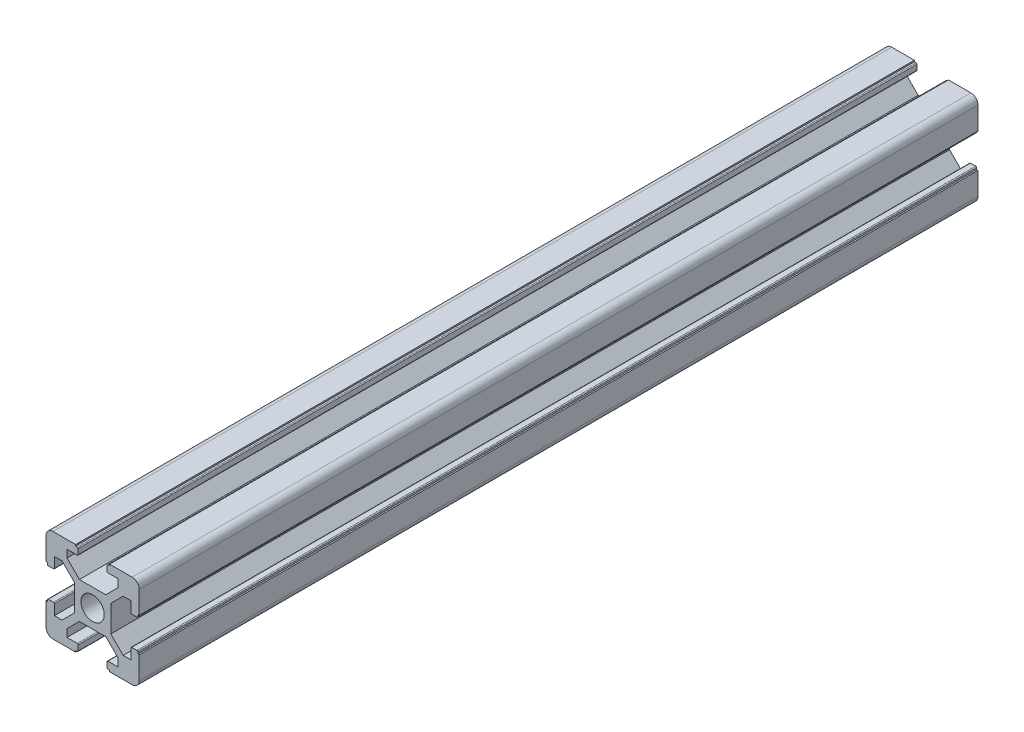
SolidWorks part; units mm, degrees
ref_plane "前视基准面" through (0, 0, 0) normal (0, 0, 1) x (1, 0, 0)
ref_plane "上视基准面" through (0, 0, 0) normal (0, 1, 0) x (1, 0, 0)
ref_plane "右视基准面" through (0, 0, 0) normal (1, 0, 0) x (0, 0, -1)
sketch "草图1" plane through (0, 0, 0) normal (0, 0, 1) x (1, 0, 0)
  line L0 (-17.5, 0) -> (33.5, 0) construction
  line L1 (0, 35.5833) -> (0, -31.0833) construction
  line L2 (3.65, 10) -> (8.5, 10)
  line L3 (10, 10) -> (10, -10) construction
  line L4 (-2.8393, 3.9) -> (2.8393, 3.9)
  line L5 (3.9, 2.8393) -> (3.9, -2.8393)
  line L6 (5.5, 8.2) -> (5.5, 6.5607)
  line L7 (3.9, 3.9) -> (10, 10) construction
  line L8 (4.4303, 3.3697) -> (6.5607, 5.5) construction
  line L9 (3.65, 10) -> (3.65, 8.2)
  line L10 (3.65, 8.2) -> (5.5, 8.2)
  line L11 (3.3697, 4.4303) -> (5.5, 6.5607) construction
  line L12 (5.5, 6.5607) -> (2.8393, 3.9)
  line L13 (6.5607, 5.5) -> (3.9, 2.8393)
  line L14 (3.3697, 4.4303) -> (9.4697, 10.5303) construction
  line L15 (4.4303, 3.3697) -> (10.5303, 9.4697) construction
  line L16 (8.2, 5.5) -> (6.5607, 5.5)
  line L17 (8.2, 3.65) -> (8.2, 5.5)
  line L18 (10, 3.65) -> (10, 8.5)
  line L19 (10, 3.65) -> (8.2, 3.65)
  line L20 (-3.3697, 4.4303) -> (-5.5, 6.5607) construction
  line L21 (-4.4303, 3.3697) -> (-6.5607, 5.5) construction
  line L22 (-3.9, 3.9) -> (-10, 10) construction
  line L23 (-10, 10) -> (-10, -10) construction
  line L24 (-10, 3.65) -> (-8.2, 3.65)
  line L25 (-10, 3.65) -> (-10, 8.5)
  line L26 (-8.2, 3.65) -> (-8.2, 5.5)
  line L27 (-8.2, 5.5) -> (-6.5607, 5.5)
  line L28 (-6.5607, 5.5) -> (-3.9, 2.8393)
  line L29 (-5.5, 6.5607) -> (-2.8393, 3.9)
  line L30 (-3.65, 8.2) -> (-5.5, 8.2)
  line L31 (-3.65, 10) -> (-3.65, 8.2)
  line L32 (-5.5, 8.2) -> (-5.5, 6.5607)
  line L33 (-3.9, 2.8393) -> (-3.9, -2.8393)
  line L34 (-3.65, 10) -> (-8.5, 10)
  line L35 (-3.9, -3.9) -> (-10, -10) construction
  line L36 (-4.4303, -3.3697) -> (-6.5607, -5.5) construction
  line L37 (-3.3697, -4.4303) -> (-5.5, -6.5607) construction
  line L38 (3.3697, -4.4303) -> (5.5, -6.5607) construction
  line L39 (4.4303, -3.3697) -> (6.5607, -5.5) construction
  line L40 (3.9, -3.9) -> (10, -10) construction
  line L41 (-3.65, -10) -> (-8.5, -10)
  line L42 (-5.5, -8.2) -> (-5.5, -6.5607)
  line L43 (-3.65, -10) -> (-3.65, -8.2)
  line L44 (-3.65, -8.2) -> (-5.5, -8.2)
  line L45 (-5.5, -6.5607) -> (-2.8393, -3.9)
  line L46 (-6.5607, -5.5) -> (-3.9, -2.8393)
  line L47 (-8.2, -5.5) -> (-6.5607, -5.5)
  line L48 (-8.2, -3.65) -> (-8.2, -5.5)
  line L49 (-10, -3.65) -> (-10, -8.5)
  line L50 (-10, -3.65) -> (-8.2, -3.65)
  line L51 (10, -3.65) -> (8.2, -3.65)
  line L52 (10, -3.65) -> (10, -8.5)
  line L53 (8.2, -3.65) -> (8.2, -5.5)
  line L54 (8.2, -5.5) -> (6.5607, -5.5)
  line L55 (6.5607, -5.5) -> (3.9, -2.8393)
  line L56 (5.5, -6.5607) -> (2.8393, -3.9)
  line L57 (3.65, -8.2) -> (5.5, -8.2)
  line L58 (3.65, -10) -> (3.65, -8.2)
  line L59 (5.5, -8.2) -> (5.5, -6.5607)
  line L60 (-2.8393, -3.9) -> (2.8393, -3.9)
  line L61 (3.65, -10) -> (8.5, -10)
  circle A0 centre (0, 0) radius 2.5
  arc A1 (-8.5, -10) -> (-10, -8.5) centre (-8.5, -8.5) cw
  arc A2 (10, -8.5) -> (8.5, -10) centre (8.5, -8.5) cw
  arc A3 (8.5, 10) -> (10, 8.5) centre (8.5, 8.5) cw
  arc A4 (-10, 8.5) -> (-8.5, 10) centre (-8.5, 8.5) cw
  point P13 (0, -3.9)
  point P42 (0, 3.9)
  point P43 (-10, 0)
  point P54 (10, 0)
  point P56 (-3.9, 0)
  point P70 (3.9, 0)
  dimension "D3" = 5
  dimension "D10" = 1.5
  dimension "D1" = 7.3
  dimension "D2" = 10
  dimension "D4" = 3.9
  dimension "D5" = 3.9
  dimension "D8" = 1.8
  dimension "D9" = 0.75
  dimension "D6" = 11
  dimension "D7" = 10
  dimension "D11" = 45
  dimension "D12" = 2.8393
extrude "凸台-拉伸2" add sketch "草图1" along normal blind 180 contours L34 A4 L25 L24 L26 L27 L28 L33 L46 L47 L48 L50 L49 A1 L41 L43 L44 L42 L45 L60 L56 L59 L57 L58 L61 A2 L52 L51 L53 L54 L55 L5 L13 L16 L17 L19 L18 A3 L2 L9 L10 L6 L12 L4 L29 L32 L30 L31
sketch "草图3" plane through (0, 0, 180) normal (0, 0, 1) x (1, 0, 0)
  line L0 (-12.6954, 0) -> (11.5012, 0) construction
  line L1 (0, 10.0863) -> (0, -11.0469) construction
  line L2 (-3.65, 8.2) -> (-3.3, 8.2)
  line L3 (3.65, 8.2) -> (3.6528, 8.2568)
  line L4 (-3.1, 8.4) -> (-3.1, 9.5)
  line L5 (3.65, 9.7) -> (3.65, 8.2)
  line L6 (-3.3, 9.7) -> (-3.65, 9.7)
  line L7 (-3.65, 8.2) -> (-3.65, 10) construction
  line L8 (-3.65, 9.7) -> (-3.65, 8.2)
  line L9 (-3.65, 8.2) -> (-3.6528, 8.2568)
  line L10 (3.3, 9.7) -> (3.65, 9.7)
  line L11 (3.1, 8.4) -> (3.1, 9.5)
  line L12 (3.65, 8.2) -> (3.3, 8.2)
  line L13 (3.65, -8.2) -> (3.3, -8.2)
  line L14 (3.1, -8.4) -> (3.1, -9.5)
  line L15 (3.3, -9.7) -> (3.65, -9.7)
  line L16 (-3.65, -8.2) -> (-3.6528, -8.2568)
  line L17 (-3.65, -9.7) -> (-3.65, -8.2)
  line L18 (-3.3, -9.7) -> (-3.65, -9.7)
  line L19 (3.65, -9.7) -> (3.65, -8.2)
  line L20 (-3.1, -8.4) -> (-3.1, -9.5)
  line L21 (3.65, -8.2) -> (3.6528, -8.2568)
  line L22 (-3.65, -8.2) -> (-3.3, -8.2)
  line L23 (0, 0) -> (9.5607, 9.5607) construction
  line L24 (-8.2, -3.65) -> (-8.2, -3.3)
  line L25 (-8.4, -3.1) -> (-9.5, -3.1)
  line L26 (-9.7, -3.3) -> (-9.7, -3.65)
  line L27 (-9.7, -3.65) -> (-8.2, -3.65)
  line L28 (-8.2, -3.65) -> (-8.2568, -3.6528)
  line L29 (8.2, 3.65) -> (8.2, 3.3)
  line L30 (8.4, 3.1) -> (9.5, 3.1)
  line L31 (9.7, 3.3) -> (9.7, 3.65)
  line L32 (9.7, 3.65) -> (8.2, 3.65)
  line L33 (8.2, 3.65) -> (8.2568, 3.6528)
  line L34 (-8.2, 3.65) -> (-8.2568, 3.6528)
  line L35 (-9.7, 3.65) -> (-8.2, 3.65)
  line L36 (-9.7, 3.3) -> (-9.7, 3.65)
  line L37 (-8.4, 3.1) -> (-9.5, 3.1)
  line L38 (-8.2, 3.65) -> (-8.2, 3.3)
  line L39 (8.2, -3.65) -> (8.2568, -3.6528)
  line L40 (9.7, -3.65) -> (8.2, -3.65)
  line L41 (9.7, -3.3) -> (9.7, -3.65)
  line L42 (8.4, -3.1) -> (9.5, -3.1)
  line L43 (8.2, -3.65) -> (8.2, -3.3)
  arc A0 (-3.1, 9.5) -> (-3.3, 9.7) centre (-3.3, 9.5) ccw
  arc A1 (-3.3, 8.2) -> (-3.1, 8.4) centre (-3.3, 8.4) ccw
  arc A2 (3.3, 8.2) -> (3.1, 8.4) centre (3.3, 8.4) cw
  arc A3 (3.1, 9.5) -> (3.3, 9.7) centre (3.3, 9.5) cw
  arc A4 (3.1, -9.5) -> (3.3, -9.7) centre (3.3, -9.5) ccw
  arc A5 (3.3, -8.2) -> (3.1, -8.4) centre (3.3, -8.4) ccw
  arc A6 (-3.3, -8.2) -> (-3.1, -8.4) centre (-3.3, -8.4) cw
  arc A7 (-3.1, -9.5) -> (-3.3, -9.7) centre (-3.3, -9.5) cw
  arc A8 (10, 8.5) -> (8.5, 10) centre (8.5, 8.5) ccw construction
  arc A9 (-9.5, -3.1) -> (-9.7, -3.3) centre (-9.5, -3.3) ccw
  arc A10 (-8.2, -3.3) -> (-8.4, -3.1) centre (-8.4, -3.3) ccw
  arc A11 (9.5, 3.1) -> (9.7, 3.3) centre (9.5, 3.3) ccw
  arc A12 (8.2, 3.3) -> (8.4, 3.1) centre (8.4, 3.3) ccw
  arc A13 (-8.2, 3.3) -> (-8.4, 3.1) centre (-8.4, 3.3) cw
  arc A14 (-9.5, 3.1) -> (-9.7, 3.3) centre (-9.5, 3.3) cw
  arc A15 (8.2, -3.3) -> (8.4, -3.1) centre (8.4, -3.3) cw
  arc A16 (9.5, -3.1) -> (9.7, -3.3) centre (9.5, -3.3) cw
  point P16 (-3.1, 9.7)
  point P19 (-3.1, 8.2)
  point P29 (3.1, 8.2)
  point P30 (3.1, 9.7)
  point P49 (3.1, -9.7)
  point P50 (3.1, -8.2)
  point P51 (-3.1, -8.2)
  point P52 (-3.1, -9.7)
  point P67 (-9.7, -3.1)
  point P68 (-8.2, -3.1)
  point P78 (9.7, 3.1)
  point P79 (8.2, 3.1)
  point P89 (-8.2, 3.1)
  point P90 (-9.7, 3.1)
  point P100 (8.2, -3.1)
  point P101 (9.7, -3.1)
  line M1 (-3.65, -10) -> (-3.65, -8.2)
  line M9 (3.65, -8.2) -> (3.65, -10)
  line M21 (8.2, 3.65) -> (10, 3.65)
  line M25 (3.65, 10) -> (3.65, 8.2)
  line M33 (-3.65, 8.2) -> (-3.65, 10)
  line M37 (-10, 3.65) -> (-8.2, 3.65)
  dimension "D3" = 0.2
  dimension "D1" = 6.2
  dimension "D2" = 1.5
extrude "凸台-拉伸3" add sketch "草图3" against normal blind 180 contours A14 L37 A13 L38 L36 M37 | L2 A1 L4 A0 L6 M33 | A3 L11 A2 L12 L10 M25 | L29 A12 L30 A11 L31 M21 | L13 A5 L14 A4 L15 M9 | A7 L20 A6 L22 L18 M1 | L43 A15 L42 A16 L41 L40 | L24 A10 L25 A9 L26 L27
